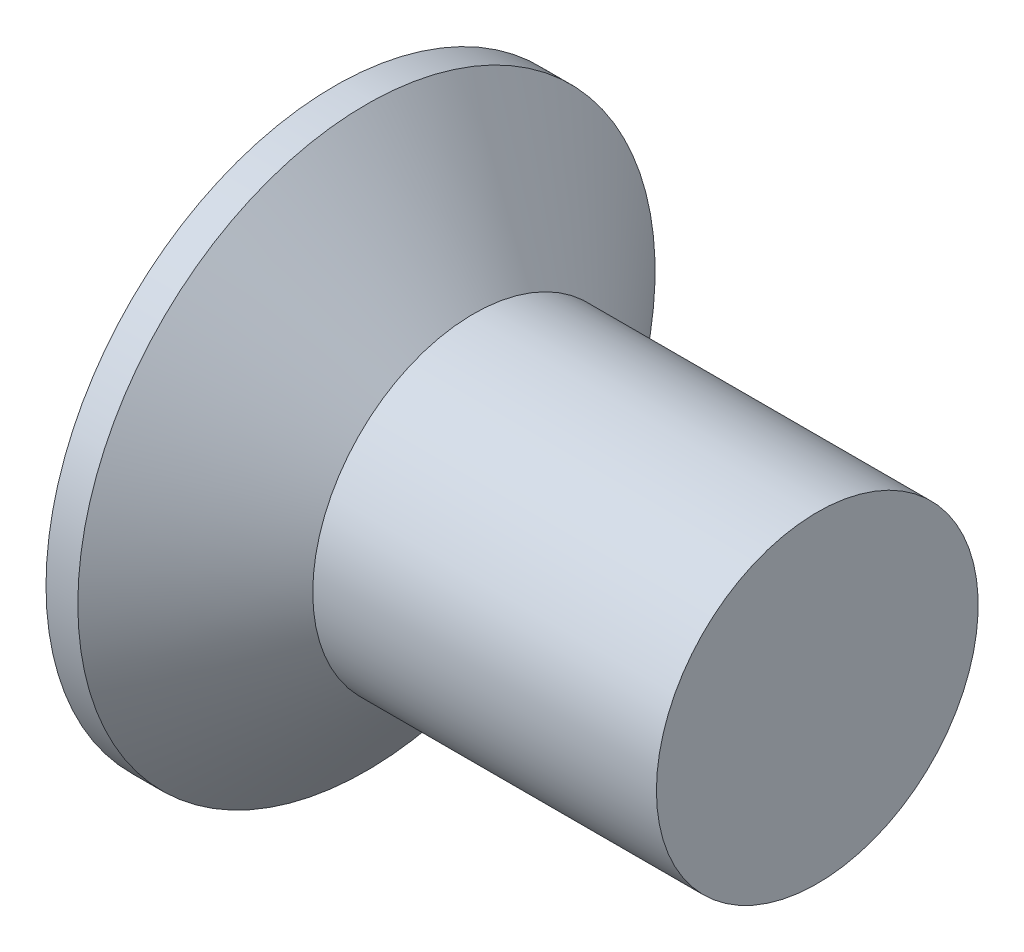
SolidWorks part; units mm, degrees
revolve "Base-Revolve" add sketch "BodySke" angle 360 about L5
sketch "BodySke" plane through (0, 0, 0) normal (0, 0, 1) x (1, 0, 0)
  line L0 (0, 0) -> (0, 11.3919)
  line L1 (0, 11.3919) -> (1.2557, 11.3919)
  line L2 (5.4864, 6.35) -> (19.05, 6.35)
  line L3 (19.05, 6.35) -> (19.05, 0)
  line L4 (19.05, 0) -> (0, 0)
  line L5 (-6.35, 0) -> (82.55, 0) construction
  line L6 (5.4864, -6.35) -> (19.05, -6.35) construction
  line L7 (1.2557, -11.3919) -> (5.4864, -6.35) construction
  line L8 (1.2557, 11.3919) -> (5.4864, 6.35)
  line L9 (0, -11.3919) -> (1.2557, -11.3919) construction
  line L10 (6.7564, 7.9375) -> (6.7564, -1.5875) construction
  line L11 (0, 6.35) -> (0, -3.175) construction
  dimension "Length" = 19.05
  dimension "Head_ang" = 100
  dimension "Thread_nom" = 19.05
cosmetic thread "ThreadCosmetic" [suppressed] parameters "Thread_length"=25.4, "Thread_minor"=11.1887
extrude "Slot" [suppressed] cut sketch "Sketch2" against normal blind 2.8194
sketch "Sketch2" plane through (0, 0, 0) normal (-1, 0, 0) x (0, 0, 1)
  line L0 (-11.3919, -1.3462) -> (11.3919, -1.3462)
  line L1 (-11.3919, -1.3462) -> (-11.3919, 1.3462)
  line L2 (11.3919, 1.3462) -> (-11.3919, 1.3462)
  line L3 (11.3919, 1.3462) -> (11.3919, -1.3462)
  dimension "D1" = 1.0668
  dimension "D2" = 13.6144
  dimension "D3" = 6.8072
ref_plane "Plane1" through (0, 0, 0) normal (0, 0, 1) x (1, 0, 0)
ref_plane "Plane2" through (0, 0, 0) normal (0, 1, 0) x (1, 0, 0)
ref_plane "Plane3" through (0, 0, 0) normal (1, 0, 0) x (0, 0, -1)
sketch "Sketch3" plane through (0, 0, 0) normal (-1, 0, 0) x (0, 0, 1)
  line L0 (-1.1811, 7.1501) -> (1.1811, 7.1501)
  line L1 (1.1811, 7.1501) -> (1.1811, -7.1501)
  line L2 (1.1811, -7.1501) -> (-1.1811, -7.1501)
  line L3 (-1.1811, -7.1501) -> (-1.1811, 7.1501)
  dimension "D1" = 4.5847
  dimension "D2" = 0.8001
ref_plane "Plane4" through (9.3218, 0, 0) normal (-1, 0, 0) x (0, 0, 1)
sketch "Sketch4" plane through (9.3218, 0, 0) normal (-1, 0, 0) x (0, 0, 1)
  line L0 (-0.5906, 0.5906) -> (0.5906, 0.5906)
  line L3 (0.5906, 0.5906) -> (0.5906, -0.5906)
  line L4 (0.5906, -0.5906) -> (-0.5906, -0.5906)
  line L5 (-0.5906, -0.5906) -> (-0.5906, 0.5906)
  dimension "D2" = 0.8001
  dimension "D1" = 0.8001
  dimension "D3" = 0.4001
  dimension "D4" = 0.4001
loft "Cross" cut profiles "Sketch3", "Sketch4"
pattern_circular "CirPattern1" count 2 every 90 about axis through (0, 0, 0) along (1, 0, 0) of "Cross"
sketch "ThdSchSke" plane through (0, 0, 0) normal (0, 0, 1) x (1, 0, 0)
  line L0 (6.7564, -5.5944) -> (6.2273, -6.35)
  line L1 (6.7564, -5.5944) -> (7.2855, -6.35)
  line L2 (7.2855, -6.35) -> (7.2855, -7.9375)
  line L3 (-3.175, 0) -> (5.1513, 0) construction
  line L5 (7.2855, -7.9375) -> (6.2273, -7.9375)
  line L6 (6.2273, -7.9375) -> (6.2273, -6.35)
  line L7 (0, 11.3919) -> (0, -11.3919) construction
  dimension "Thread_minor" = 6.6777
  dimension "Diameter" = 7.9375
  dimension "Start" = 25.4
revolve "ThreadSchematic" [suppressed] cut sketch "ThdSchSke" angle 360 about L3
pattern_linear "ThdSchPat" [suppressed]
equation "\"D1@Sketch3\" = \"Cross_dia@Sketch3\" / 2"
equation "\"D2@Sketch3\" = \"Cross_width@Sketch3\" / 2"
equation "\"D1@Sketch4\" = \"Cross_width@Sketch3\" *.5"
equation "\"D2@Sketch4\" = \"D1@Sketch4\""
equation "\"D4@Sketch4\" = \"D2@Sketch4\" / 2"
equation "\"D3@Sketch4\" = \"D1@Sketch4\" / 2"
equation "\"D1@Sketch2\" = \"Slot_width@Sketch2\" / 2"
equation "\"D2@Sketch2\" = \"Head_dia@BodySke\""
equation "\"D3@Sketch2\" = \"D2@Sketch2\" / 2"
equation "\"Thread_length@ThreadCosmetic\" = ((sgn( (\"Length@BodySke\" - \"Advance@BodySke\" - \"Head_ht@BodySke\" ) - \"Thread_nom@BodySke\" )-1)*( (\"Length@BodySke\" - \"Advance@BodySke\" - \"Head_ht@BodySke\" ) - \"Thread_nom@BodySke\" ))/-2+ \"Thread_nom@BodySke\""
equation "\"Thread_minor@ThdSchSke\" = \"Thread_minor@ThreadCosmetic\""
equation "\"Diameter@ThdSchSke\" = \"Diameter@BodySke\""
equation "\"Overcut@ThdSchSke\" = \"Diameter@BodySke\" * 1.25"
equation "\"Start@ThdSchSke\" = 0.000001 + \"Length@BodySke\" - \"Thread_length@ThreadCosmetic\"  '---Countersunk---"
equation "\"Num_threads@ThdSchPat\" = int( \"Thread_length@ThreadCosmetic\" / \"Advance@BodySke\" + 0.999 )  + 1"
equation "\"Advance@ThdSchPat\" = \"Thread_length@ThreadCosmetic\" /  (\"Num_threads@ThdSchPat\" - 1) 'relax it"
